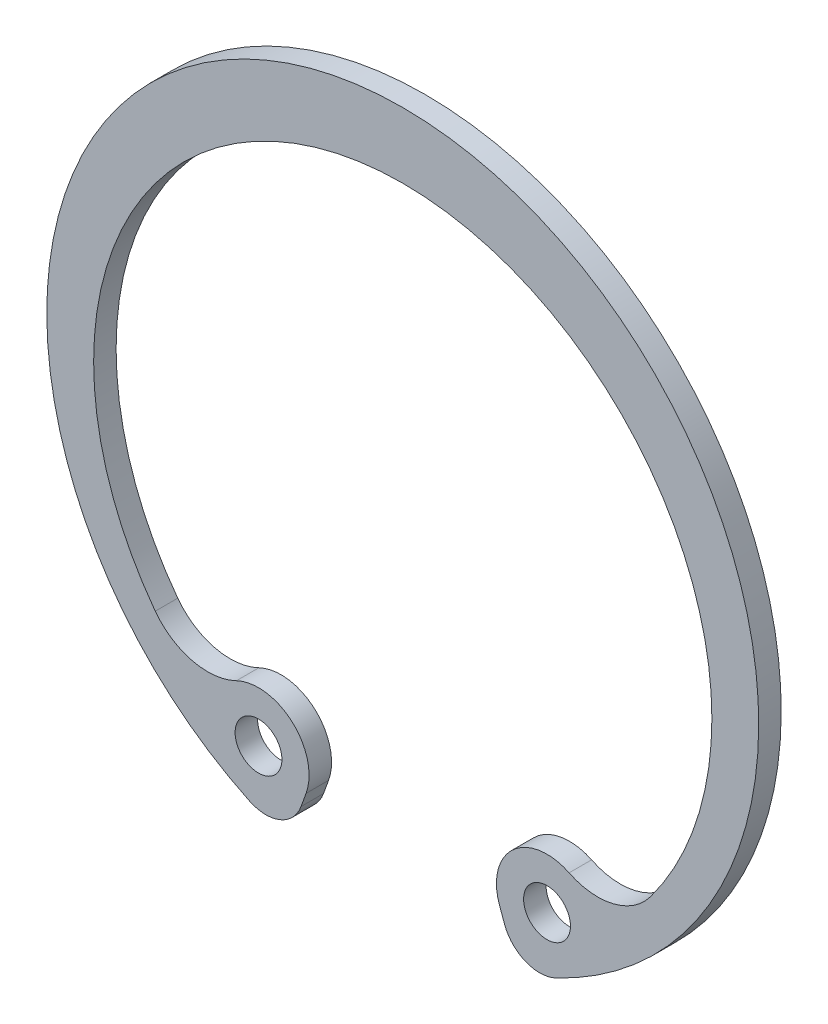
SolidWorks part; units mm, degrees
material "Простая углеродистая сталь"
ref_plane "Front" through (0, 0, 0) normal (0, 0, 1) x (1, 0, 0)
ref_plane "Top" through (0, 0, 0) normal (0, 1, 0) x (1, 0, 0)
ref_plane "Right" through (0, 0, 0) normal (1, 0, 0) x (0, 0, -1)
sketch "Эскиз1" plane through (0, 0, 0) normal (0, 0, 1) x (1, 0, 0)
  line L0 (0, 16.1701) -> (0, -23.5361) construction
  line L1 (-5.1606, -15.2841) -> (-5.4293, -16.0275)
  line L2 (5.1606, -15.2841) -> (5.4293, -16.0275)
  arc A0 (8.1703, -17.1536) -> (-8.1703, -17.1536) centre (0, 0) ccw
  arc A1 (13.2102, -10.8864) -> (-13.2102, -10.8864) centre (0, -1) ccw
  arc A2 (-5.1606, -15.2841) -> (-8.8793, -11.9378) centre (-7.7, -14.3666) ccw
  arc A3 (-13.2102, -10.8864) -> (-8.8793, -11.9378) centre (-10.408, -8.7893) ccw
  arc A4 (-5.4293, -16.0275) -> (-8.1703, -17.1536) centre (-7.3103, -15.348) cw
  arc A5 (5.4293, -16.0275) -> (8.1703, -17.1536) centre (7.3103, -15.348) ccw
  arc A6 (13.2102, -10.8864) -> (8.8793, -11.9378) centre (10.408, -8.7893) cw
  arc A7 (5.1606, -15.2841) -> (8.8793, -11.9378) centre (7.7, -14.3666) cw
  circle A8 centre (-7.7, -14.3666) radius 1.25
  circle A9 centre (7.7, -14.3666) radius 1.25
  dimension "D1" = 38
  dimension "D2" = 1
  dimension "D3" = 33
  dimension "D4" = 5.4
  dimension "D5" = 3.5
  dimension "D6" = 2
  dimension "D7" = 10
  dimension "D8" = 2.5
extrude "Бобышка-Вытянуть1" add sketch "Эскиз1" along normal blind 1.2
